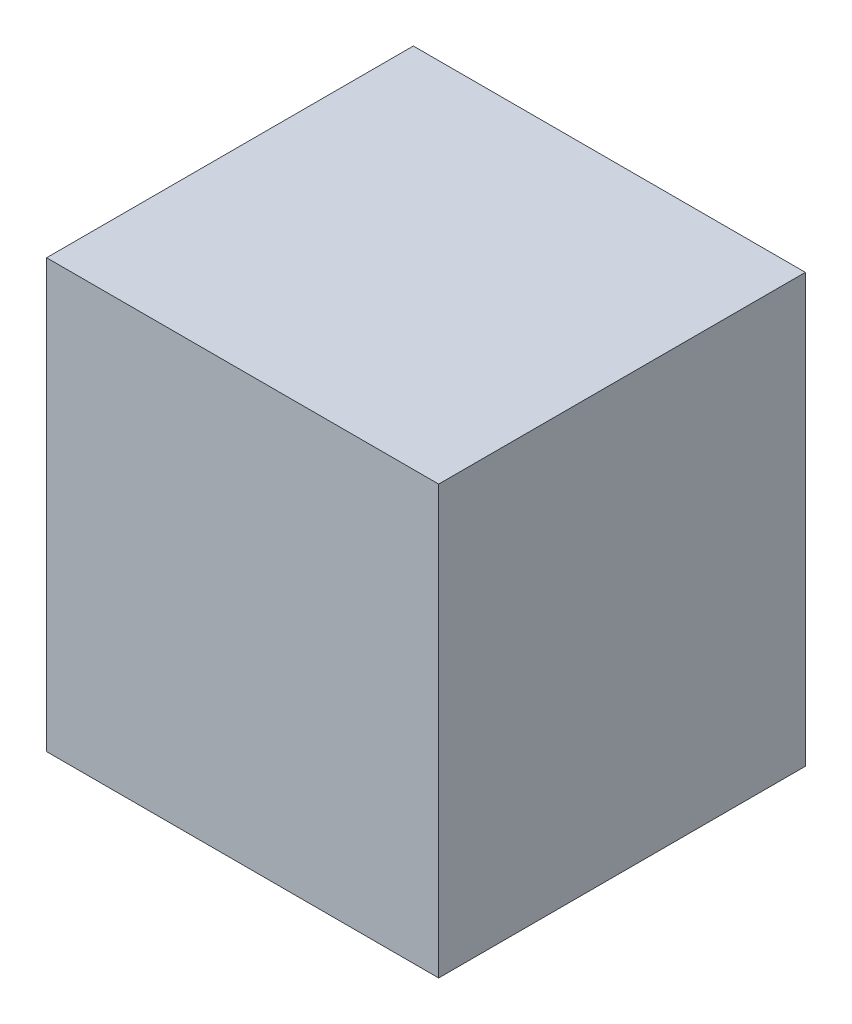
SolidWorks part; units mm, degrees
ref_plane "Front Plane" through (0, 0, 0) normal (1, 0, 0) x (0, 1, 0)
ref_plane "Top Plane" through (0, 0, 0) normal (0, 0, 1) x (0, 1, 0)
ref_plane "Right Plane" through (0, 0, 0) normal (0, 1, 0) x (-1, 0, 0)
sketch "Sketch1" plane through (0, 0, 0) normal (1, 0, 0) x (0, 1, 0)
  line L1 (0, 0) -> (119.988, 0)
  line L2 (0, 0) -> (0, 129.794)
  line L3 (0, 129.794) -> (119.988, 129.794)
  line L4 (119.988, 0) -> (119.988, 129.794)
  dimension "D1" = 129.794
  dimension "D2" = 119.988
extrude "Boss-Extrude1" add sketch "Sketch1" against normal blind 104.9976 and the other way blind 4.9789
sketch "Sketch3" plane through (0, 0, 0) normal (0, 0, -1) x (1, 0, 0)
  circle A0 centre (-50.038, -59.994) radius 4
  point P2 (0, 0)
  dimension "D1" = 8
extrude "Cut-Extrude1" cut sketch "Sketch3" against normal blind 26.924 flip side to cut
sketch "Sketch4" plane through (0, 0, 0) normal (0, -1, 0) x (1, 0, 0)
  line L0 (-50.0094, 26.924) -> (-50.0094, 129.794) construction
  line L2 (-104.9976, 129.794) -> (4.9789, 129.794) construction
  line L3 (-97.538, 33.924) -> (-2.4807, 33.924) construction
  line L4 (-97.538, 75.924) -> (-2.4807, 75.924) construction
  line L5 (-104.9976, 26.924) -> (4.9789, 26.924) construction
  circle A0 centre (-97.538, 33.924) radius 2.8
  circle A1 centre (-97.538, 75.924) radius 2.8
  circle A2 centre (-2.4807, 75.924) radius 2.8
  circle A3 centre (-2.4807, 33.924) radius 2.8
  point P9 (-50.0094, 33.924)
  point P12 (-50.0094, 75.924)
  point P15 (0, 0)
  point P16 (0, 0)
  point P18 (0, 0)
  point P19 (-97.538, 75.7773)
  point P20 (0, 0)
  point P22 (-2.5011, 75.9582)
  point P25 (-2.538, 33.8825)
  dimension "D1" = 42
  dimension "D2" = 7
extrude "Cut-Extrude2" cut sketch "Sketch4" against normal blind 5 contours A0 | A1 | A2 | A3
ref_plane "Plane1" through (0, 0, 12.5) normal (0, 0, -1) x (-1, 0, 0)
